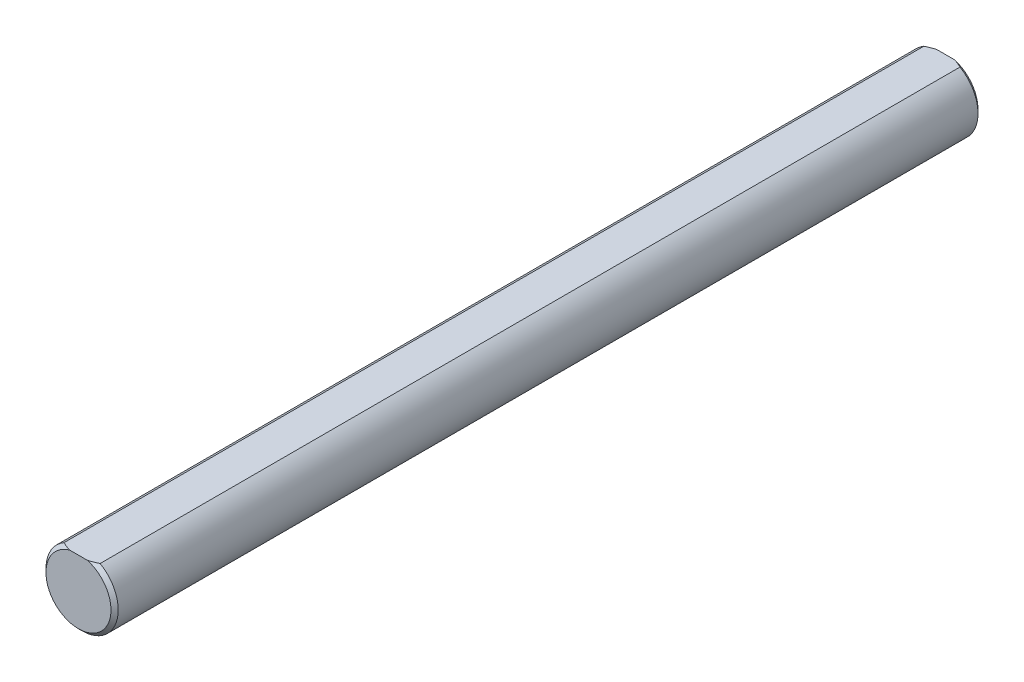
SolidWorks part; units mm, degrees
ref_plane "Front Plane" through (0, 0, 0) normal (0, 0, 1) x (1, 0, 0)
ref_plane "Top Plane" through (0, 0, 0) normal (0, 1, 0) x (1, 0, 0)
ref_plane "Right Plane" through (0, 0, 0) normal (1, 0, 0) x (0, 0, -1)
sketch "Sketch1" plane through (0, 0, 0) normal (0, 0, 1) x (1, 0, 0)
  circle A1 centre (0, 0) radius 6.35 construction
  dimension "Diameter" = 12.7
sketch "Sketch2" plane through (0, 0, 0) normal (1, 0, 0) x (0, 0, -1)
  line L0 (-76.2, 6.35) -> (76.2, 6.35) construction
  line L1 (0, 6.35) -> (0, -6.35) construction
  line L2 (0, 6.35) -> (0, -6.35) construction
  point P2 (0, 6.35)
  point P3 (50.8, 6.35)
  point P4 (-50.8, 6.35)
  dimension "Length" = 152.4
  dimension "D2" = 25.4
  dimension "D1" = 25.4
sketch "Sketch3" plane through (0, 0, 0) normal (0, 0, 1) x (1, 0, 0)
  circle A1 centre (0, 0) radius 6.35 construction
  circle A3 centre (0, 0) radius 6.35
extrude "Boss-Extrude2" add sketch "Sketch3" along normal up to vertex (76.2 mm away) and the other way up to vertex (76.2 mm away) up to point (0, 6.35, 76.2) other way up to point (0, 6.35, -76.2)
sketch "Sketch10" plane through (0, 0, 0) normal (0, 0, 1) x (1, 0, 0)
  line L0 (-3.175, 5.4993) -> (3.175, 5.4993)
  line L1 (0, 0) -> (0, 6.35) construction
  circle A0 centre (0, 0) radius 6.35 construction
  circle A1 centre (0, 0) radius 6.35 construction
  arc A2 (-3.175, 5.4993) -> (3.175, 5.4993) centre (0, 0) cw
extrude "Cut-Extrude5" cut sketch "Sketch10" against normal through all both and the other way through all
chamfer "Chamfer1" distance 0.635 angle 45 4 edges at (0, -6.35, 76.2) (0, -6.35, -76.2) (0, 5.4993, -76.2) (0, 5.4993, 76.2)
equation "\"D1@Chamfer1\"= \"Diameter@Sketch1\" / 20"
equation "\"D1@Sketch2\"=\"Diameter@Sketch1\"*2"
equation "\"D2@Sketch2\"=\"D1@Sketch2\""
